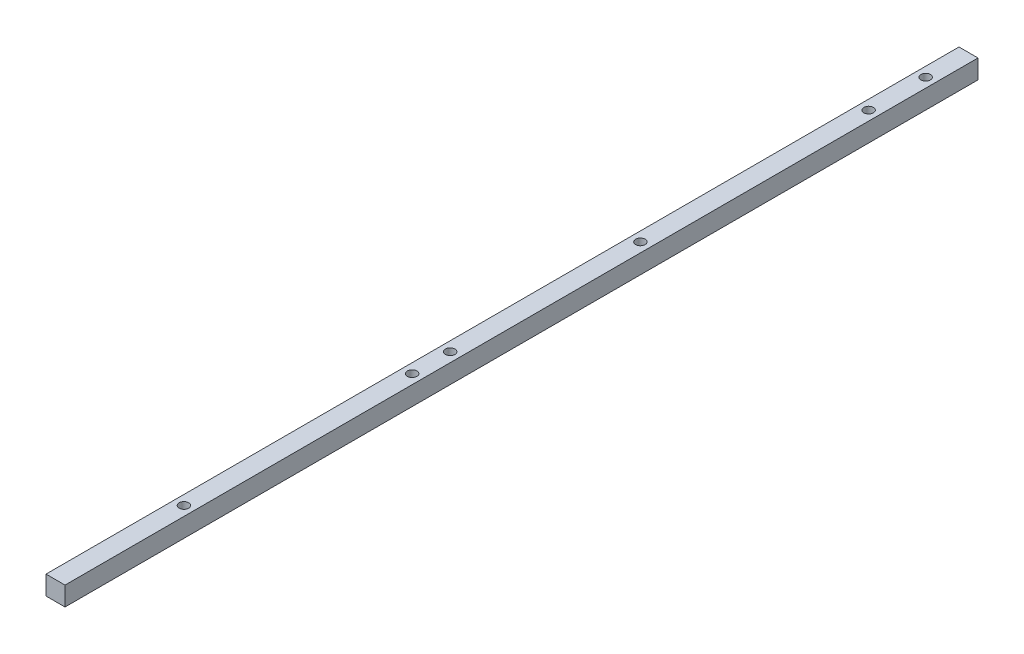
SolidWorks part; units mm, degrees
ref_plane "Front Plane" through (0, 0, 0) normal (0, 0, 1) x (1, 0, 0)
ref_plane "Top Plane" through (0, 0, 0) normal (0, 1, 0) x (1, 0, 0)
ref_plane "Right Plane" through (0, 0, 0) normal (1, 0, 0) x (0, 0, -1)
sketch "Sketch1" plane through (0, 0, 0) normal (0, 1, 0) x (1, 0, 0)
  line L0 (-86.5656, 309.5625) -> (72.1277, 309.5625) construction
  line L1 (0, 0) -> (6.35, 0)
  line L2 (0, 0) -> (0, 304.8)
  line L3 (0, 304.8) -> (6.35, 304.8)
  line L4 (6.35, 0) -> (6.35, 304.8)
  circle A0 centre (3.175, 271.4625) radius 1.5875
  circle A1 centre (3.175, 195.2625) radius 1.5875
  circle A2 centre (3.175, 119.0625) radius 1.5875
  circle A3 centre (3.175, 42.8625) radius 1.5875
  circle A4 centre (3.175, 290.5125) radius 1.5875
  circle A5 centre (3.175, 131.7625) radius 1.5875
  point P7 (3.175, 304.8)
  dimension "D4" = 3.175
  dimension "D8" = 3.175
  dimension "D1" = 304.8
  dimension "D2" = 6.35
  dimension "D3" = 38.1
  dimension "D6" = 19.05
  dimension "D7" = 4.7625
  dimension "D9" = 158.75
  dimension "D5" = 4
extrude "Boss-Extrude1" add sketch "Sketch1" along normal blind 6.35
